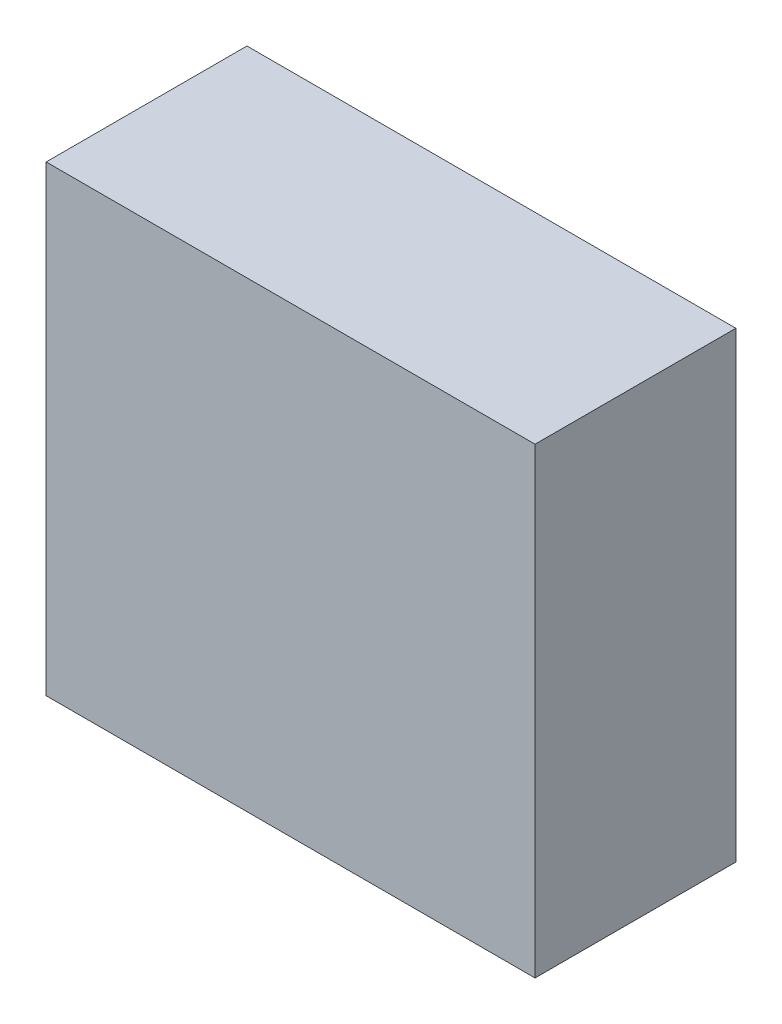
SolidWorks part; units mm, degrees
ref_plane "Front Plane" through (0, 0, 0) normal (0, 0, 1) x (1, 0, 0)
ref_plane "Top Plane" through (0, 0, 0) normal (0, 1, 0) x (1, 0, 0)
ref_plane "Right Plane" through (0, 0, 0) normal (1, 0, 0) x (0, 0, -1)
sketch "Sketch1" plane through (0, 0, 0) normal (0, 0, 1) x (1, 0, 0)
  line L1 (-21.425, -20.26) -> (21.425, -20.26)
  line L2 (-21.425, -20.26) -> (-21.425, 20.26)
  line L3 (-21.425, 20.26) -> (21.425, 20.26)
  line L4 (21.425, -20.26) -> (21.425, 20.26)
  line L5 (-21.425, -20.26) -> (21.425, 20.26) construction
  line L6 (-21.425, 20.26) -> (21.425, -20.26) construction
  point P0 (0, 0)
extrude "Envelope" add sketch "Sketch1" along normal blind 17.6
